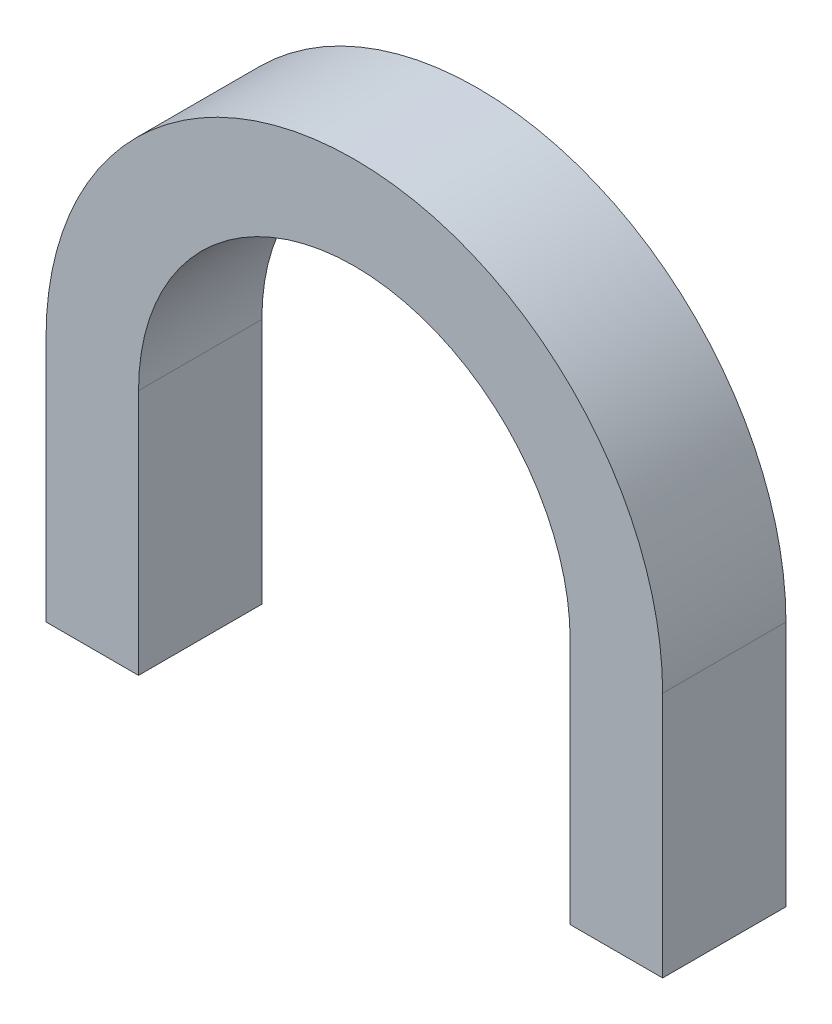
SolidWorks part; units mm, degrees
ref_plane "Front Plane" through (0, 0, 0) normal (0, 0, 1) x (1, 0, 0)
ref_plane "Top Plane" through (0, 0, 0) normal (0, 1, 0) x (1, 0, 0)
ref_plane "Right Plane" through (0, 0, 0) normal (1, 0, 0) x (0, 0, -1)
sketch "Sketch1" plane through (0, 0, 0) normal (0, 0, 1) x (1, 0, 0)
  line L0 (-5, 0) -> (-5, 4)
  line L1 (0, 10.4557) -> (0, -6.4557) construction
  line L2 (-9.8987, 0) -> (15.1139, 0) construction
  line L3 (5, 4) -> (5, 0)
  line L4 (-7.6203, 4) -> (10.8608, 4) construction
  line L5 (-3.5, 0) -> (-3.5, 4)
  line L6 (3.5, 4) -> (3.5, 0)
  line L7 (-5, 0) -> (-3.5, 0)
  line L8 (3.5, 0) -> (5, 0)
  arc A0 (-5, 4) -> (5, 4) centre (0, 4) cw
  arc A1 (-3.5, 4) -> (3.5, 4) centre (0, 4) cw
  dimension "D1" = 5
  dimension "D2" = 3.5
  dimension "D3" = 4
extrude "Boss-Extrude1" add sketch "Sketch1" along normal blind 2
